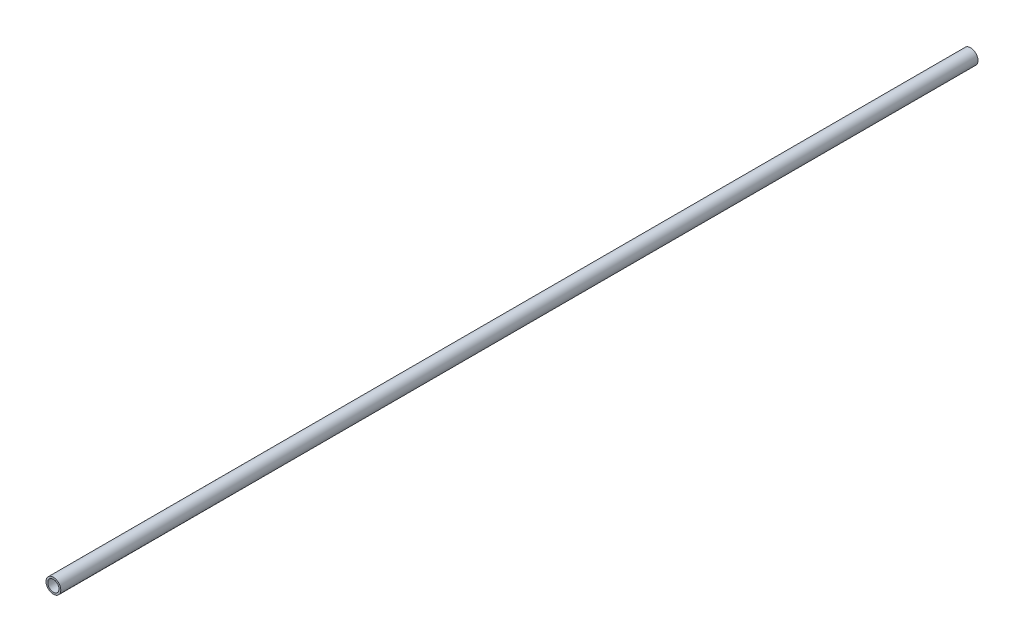
SolidWorks part; units mm, degrees
material "Plain Carbon Steel"
ref_plane "Front Plane" through (0, 0, 0) normal (0, 0, 1) x (1, 0, 0)
ref_plane "Top Plane" through (0, 0, 0) normal (0, 1, 0) x (1, 0, 0)
ref_plane "Right Plane" through (0, 0, 0) normal (1, 0, 0) x (0, 0, -1)
sketch "Sketch1" plane through (0, 0, 0) normal (0, 0, 1) x (1, 0, 0)
  circle A0 centre (0, 0) radius 12.7
  circle A1 centre (0, 0) radius 16.7005
extrude "Boss-Extrude1" add sketch "Sketch1" along normal blind 2072.386
